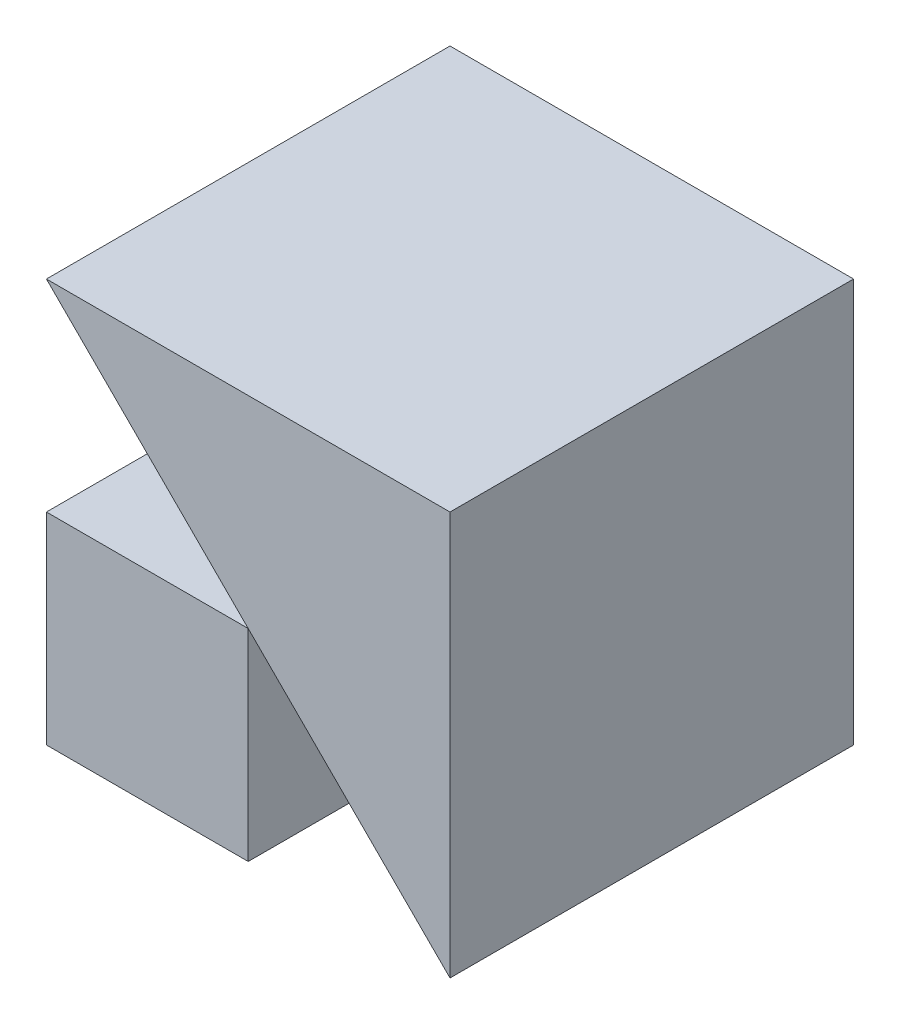
SolidWorks part; units mm, degrees
ref_plane "Front Plane" through (0, 0, 0) normal (0, 0, 1) x (1, 0, 0)
ref_plane "Top Plane" through (0, 0, 0) normal (0, 1, 0) x (1, 0, 0)
ref_plane "Right Plane" through (0, 0, 0) normal (1, 0, 0) x (0, 0, -1)
sketch "Sketch1" plane through (0, 0, 0) normal (0, 0, 1) x (1, 0, 0)
  line L0 (0, 0) -> (4, -4)
  line L1 (0, 0) -> (4, 0)
  line L4 (4, 0) -> (4, -4)
  line L6 (2, -4) -> (2, -2)
  line L7 (2, -2) -> (0, -2)
  line L8 (0, -2) -> (0, -4)
  line L9 (0, -4) -> (2, -4)
  dimension "D1" = 4
  dimension "D2" = 2
  dimension "D3" = 45
  dimension "D4" = 45
  dimension "D5" = 2
  dimension "D6" = 4
  dimension "D7" = 2
extrude "Boss-Extrude1" add sketch "Sketch1" along normal blind 4
